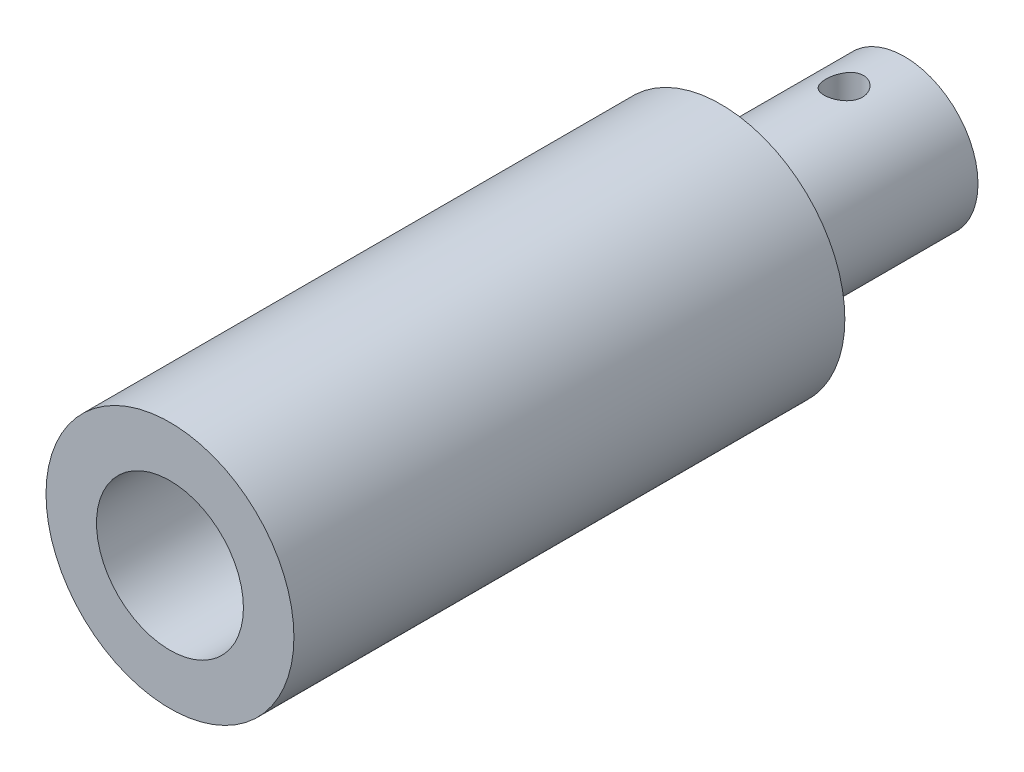
SolidWorks part; units mm, degrees
material "AISI 304"
ref_plane "Front" through (0, 0, 0) normal (0, 0, 1) x (1, 0, 0)
ref_plane "Top" through (0, 0, 0) normal (0, 1, 0) x (1, 0, 0)
ref_plane "Right" through (0, 0, 0) normal (1, 0, 0) x (0, 0, -1)
sketch "Sketch1" plane through (0, 0, 0) normal (0, 0, 1) x (1, 0, 0)
  circle A0 centre (0, 0) radius 6.75
  dimension "D1" = 13.5
extrude "Boss-Extrude1" add sketch "Sketch1" along normal blind 30
sketch "Sketch3" plane through (0, 0, 0) normal (0, 0, -1) x (-1, 0, 0)
  circle A0 centre (0, 0) radius 4
  dimension "D1" = 8
extrude "Boss-Extrude4" add sketch "Sketch3" along normal blind 10
ref_plane "Plane1" through (0, 4, 0) normal (0, 1, 0) x (1, 0, 0)
sketch "Sketch4" plane through (0, 4, 0) normal (0, 1, 0) x (1, 0, 0)
  line L0 (4, 10) -> (-4, 10) construction
  circle A0 centre (-0.2914, 7) radius 1
  dimension "D1" = 2
  dimension "D2" = 3
extrude "Cut-Extrude2" cut sketch "Sketch4" against normal blind 15
sketch "Sketch2" plane through (0, 0, 30) normal (0, 0, 1) x (1, 0, 0)
  circle A0 centre (0, 0) radius 4
  dimension "D1" = 8
extrude "Cut-Extrude3" cut sketch "Sketch2" against normal blind 25
